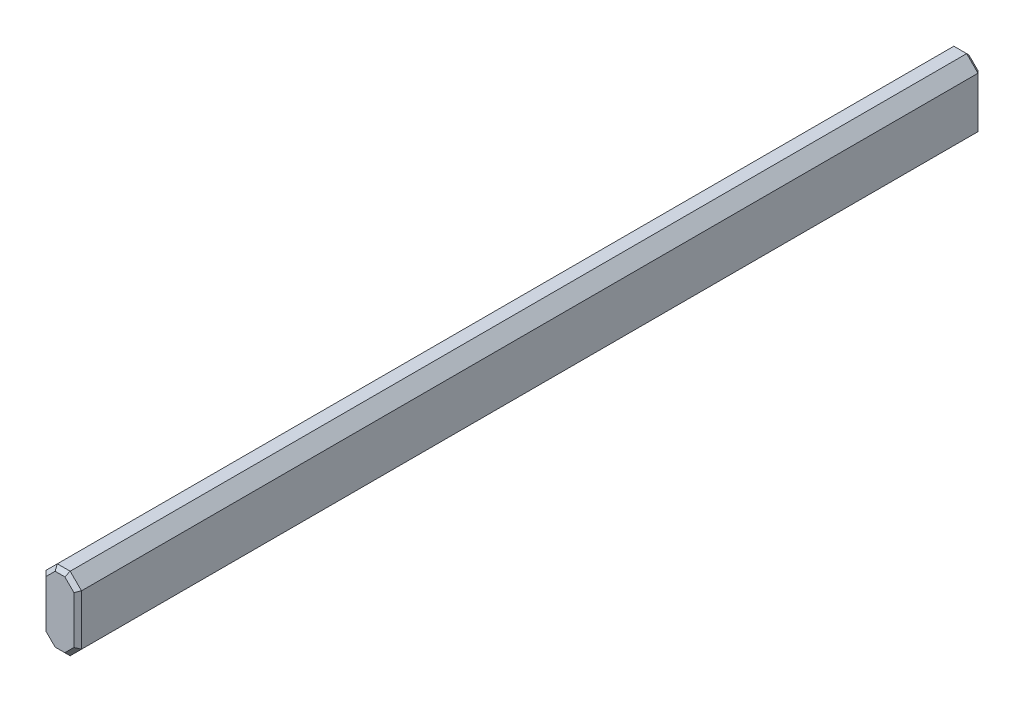
SolidWorks part; units mm, degrees
ref_plane "Plano frontal" through (0, 0, 0) normal (0, 0, 1) x (1, 0, 0)
ref_plane "Plano superior" through (0, 0, 0) normal (0, 1, 0) x (1, 0, 0)
ref_plane "Plano direito" through (0, 0, 0) normal (1, 0, 0) x (0, 0, -1)
sketch "Esboço1" plane through (0, 0, 0) normal (0, 0, 1) x (1, 0, 0)
  line L1 (2.5, 5) -> (-2.5, 5)
  line L2 (2.5, 5) -> (2.5, -5)
  line L3 (2.5, -5) -> (-2.5, -5)
  line L4 (-2.5, 5) -> (-2.5, -5)
  point P0 (0, 0)
  dimension "D1" = 10
  dimension "D2" = 5
sketch "Esboço2" plane through (0, 0, 0) normal (0, 0, 1) x (1, 0, 0)
  line L8 (2.35, 4.85) -> (-2.35, 4.85)
  line L9 (2.35, -4.85) -> (2.35, 4.85)
  line L10 (-2.35, -4.85) -> (2.35, -4.85)
  line L11 (-2.35, 4.85) -> (-2.35, -4.85)
  line L12 (2.35, 4.85) -> (-2.35, 4.85)
  line L13 (2.35, -4.85) -> (2.35, 4.85)
  line L14 (-2.35, -4.85) -> (2.35, -4.85)
  line L15 (-2.35, 4.85) -> (-2.35, -4.85)
  dimension "D1" = 0.15
extrude "Ressalto-extrusão1" add sketch "Esboço2" along normal blind 119.7
chamfer "Chanfro1" distance 1.5 angle 45 4 edges at (-2.35, -4.85, 59.85) (-2.35, 4.85, 59.85) (2.35, -4.85, 59.85) (2.35, 4.85, 59.85)
chamfer "Chanfro2" distance 0.5 angle 45 16 edges at (-1.6, 4.1, 119.7) (0, 4.85, 119.7) (1.6, 4.1, 119.7) (2.35, 0, 119.7) (1.6, -4.1, 119.7) (0, -4.85, 119.7) (-1.6, -4.1, 119.7) (-2.35, 0, 119.7) (1.6, -4.1, 0) (2.35, 0, 0) (1.6, 4.1, 0) (0, 4.85, 0) (-1.6, 4.1, 0) (-2.35, 0, 0) (-1.6, -4.1, 0) (0, -4.85, 0)
